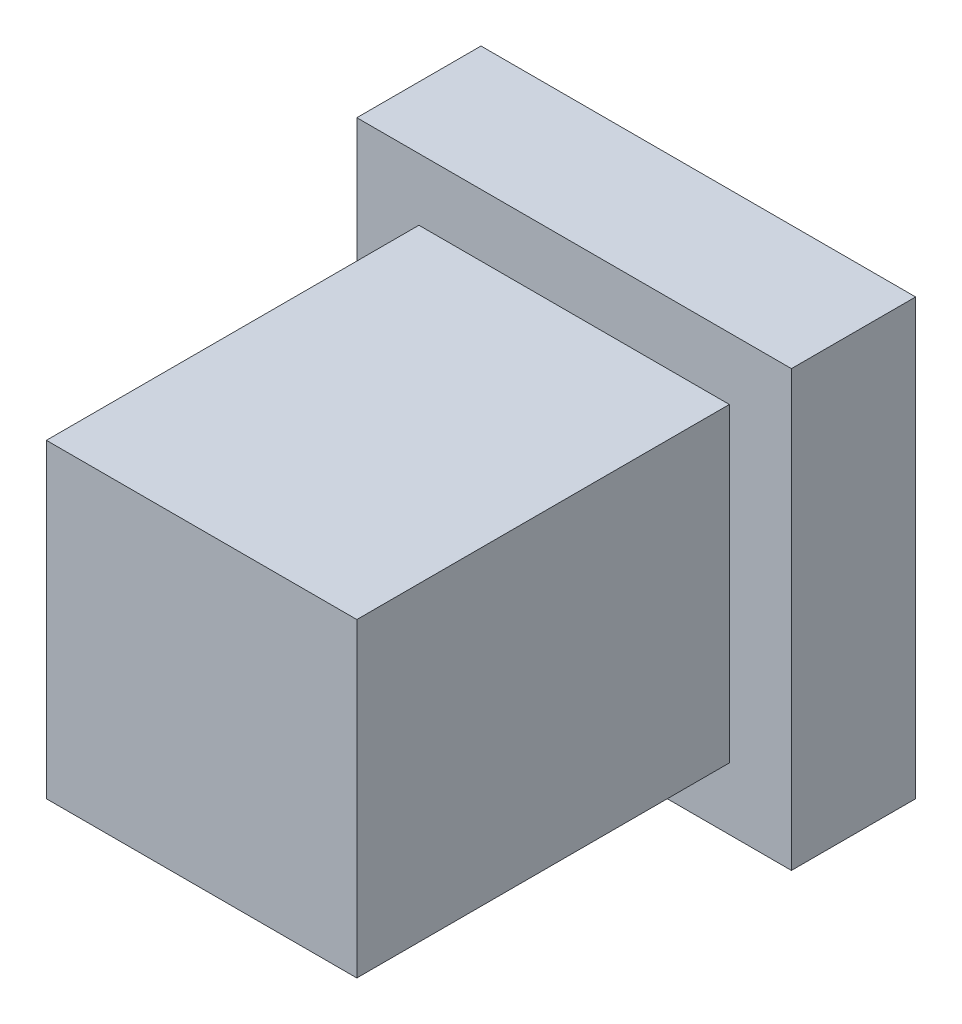
SolidWorks part; units mm, degrees
ref_plane "前视基准面" through (0, 0, 0) normal (0, 0, 1) x (1, 0, 0)
ref_plane "上视基准面" through (0, 0, 0) normal (0, 1, 0) x (1, 0, 0)
ref_plane "右视基准面" through (0, 0, 0) normal (1, 0, 0) x (0, 0, -1)
sketch "草图1" plane through (0, 0, 0) normal (0, 0, 1) x (1, 0, 0)
  line L9 (-2.5, -2.5) -> (2.5, -2.5)
  line L10 (-2.5, -2.5) -> (-2.5, 2.5)
  line L11 (-2.5, 2.5) -> (2.5, 2.5)
  line L12 (2.5, -2.5) -> (2.5, 2.5)
  line L13 (-2.5, -2.5) -> (2.5, 2.5) construction
  line L14 (-2.5, 2.5) -> (2.5, -2.5) construction
  point P0 (0, 0)
  dimension "D1" = 5
extrude "凸台-拉伸1" add sketch "草图1" along normal blind 8
sketch "草图2" plane through (0, 0, 0) normal (0, 0, -1) x (-1, 0, 0)
  line L1 (-3.5, -3.5) -> (3.5, -3.5)
  line L2 (-3.5, -3.5) -> (-3.5, 3.5)
  line L3 (-3.5, 3.5) -> (3.5, 3.5)
  line L4 (3.5, -3.5) -> (3.5, 3.5)
  line L5 (-3.5, -3.5) -> (3.5, 3.5) construction
  line L6 (-3.5, 3.5) -> (3.5, -3.5) construction
  point P0 (0, 0)
  dimension "D1" = 7
extrude "凸台-拉伸2" add sketch "草图2" against normal blind 2
sketch "草图3" plane through (0, 0, 0) normal (0, 0, -1) x (-1, 0, 0)
  circle A0 centre (0, 0) radius 1.5
  dimension "D1" = 3
extrude "切除-拉伸1" cut sketch "草图3" against normal blind 5
